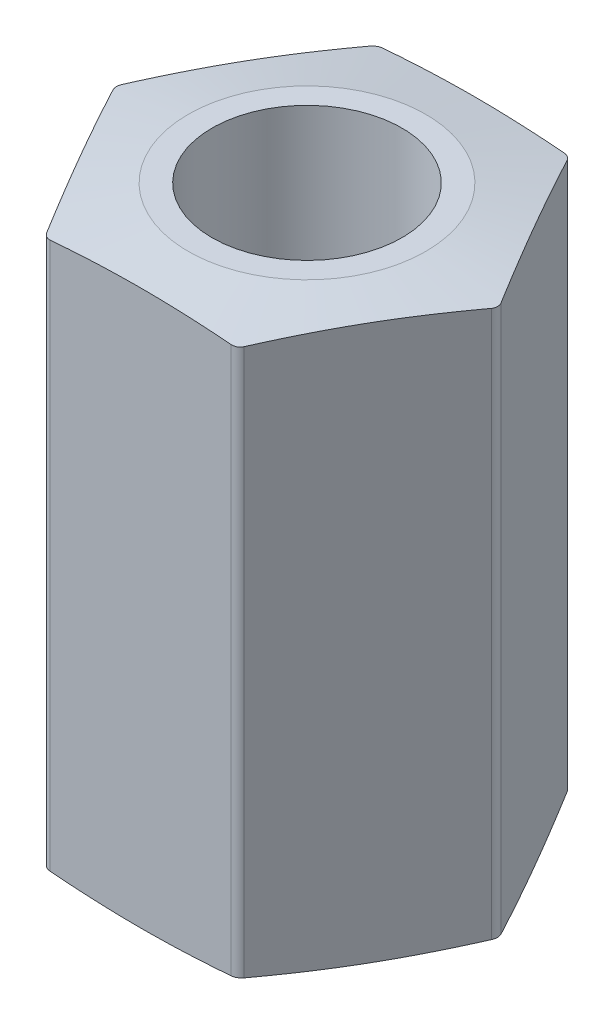
SolidWorks part; units mm, degrees
material "6063-O，挤压棒材(SS)"
ref_plane "前视基准面" through (0, 0, 0) normal (0, 0, 1) x (1, 0, 0)
ref_plane "上视基准面" through (0, 0, 0) normal (0, 1, 0) x (1, 0, 0)
ref_plane "右视基准面" through (0, 0, 0) normal (1, 0, 0) x (0, 0, -1)
sketch "草图1" plane through (0, 0, 0) normal (0, 1, 0) x (1, 0, 0)
  line L1 (4.0415, 0) -> (2.0207, 3.5)
  line L2 (2.0207, 3.5) -> (-2.0207, 3.5)
  line L3 (-2.0207, 3.5) -> (-4.0415, 0)
  line L4 (-4.0415, 0) -> (-2.0207, -3.5)
  line L5 (-2.0207, -3.5) -> (2.0207, -3.5)
  line L6 (2.0207, -3.5) -> (4.0415, 0)
  circle A0 centre (0, 0) radius 3.5 construction
  dimension "六角对边距离" = 7
extrude "凸台-拉伸1" add sketch "草图1" along normal mid plane 12
fillet "圆角1" radius 0.2 6 edges at (2.0207, 0, -3.5) (-4.0415, 0, 0) (-2.0207, 0, -3.5) (-2.0207, 0, 3.5) (4.0415, 0, 0) (2.0207, 0, 3.5)
sketch "草图3" plane through (0, 6, 0) normal (0, 1, 0) x (1, 0, 0)
  circle A0 centre (0, 0) radius 2
  dimension "螺纹公称尺寸" = 4
extrude "切除-拉伸1" cut sketch "草图3" against normal blind 8
sketch "草图4" plane through (0, 0, 0) normal (0, 0, 1) x (1, 0, 0)
  line L0 (-2, 6) -> (-4.0105, 6) construction
  line L1 (-1.9053, 6) -> (1.9053, 6) construction
  line L2 (-4.0105, 6) -> (-4.0105, 5.75)
  line L4 (-4.0105, 6) -> (-4.0105, -6) construction
  line L5 (-2, 0.161) -> (-2, 8.9742) construction
  line L9 (-4.0105, 5.75) -> (-2.5, 6)
  line L10 (-2.5, 6) -> (-4.0105, 6)
  line L11 (0, 0) -> (0, 6) construction
  dimension "D1" = 0.25
  dimension "D2" = 0.5
revolve "切除-旋转1" cut sketch "草图4" angle 360 about L11
mirror "镜向1" about plane through (0, 0, 0) normal (0, 1, 0) of "切除-旋转1", "切除-拉伸1"
other "冻结***"
